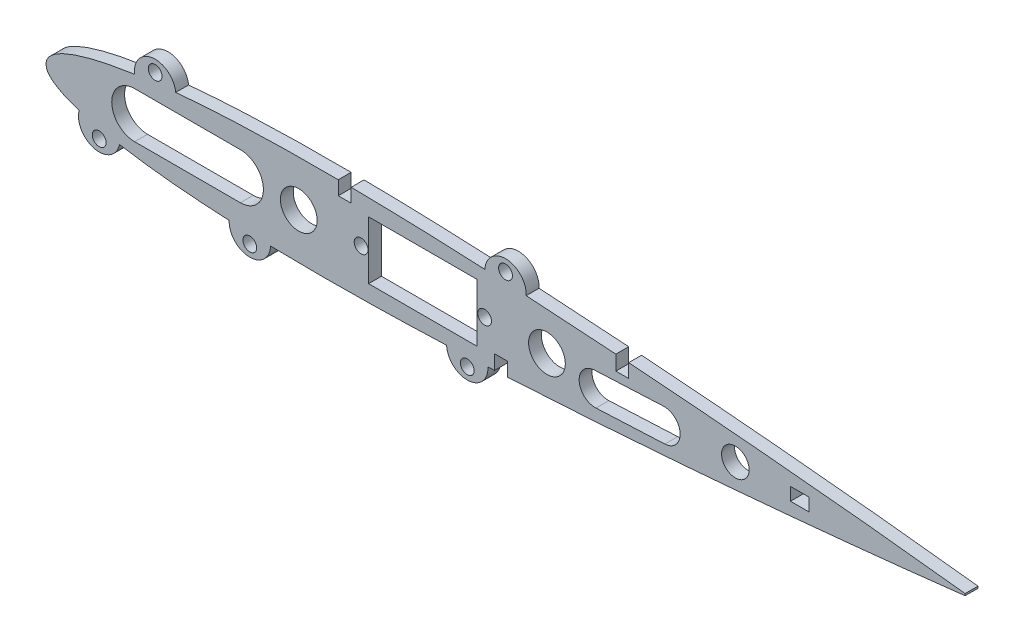
SolidWorks part; units mm, degrees
material "Фанера"
ref_plane "Спереди" through (0, 0, 0) normal (0, 0, 1) x (1, 0, 0)
ref_plane "Сверху" through (0, 0, 0) normal (0, 1, 0) x (1, 0, 0)
ref_plane "Справа" through (0, 0, 0) normal (1, 0, 0) x (0, 0, -1)
curve "Кривая1"
  spline degree 3 poles (200, 0.21, 0) (199.5201, 0.266, 0) (198.1795, 0.4223, 0) (195.7476, 0.7017, 0) (192.5308, 1.0651, 0) (188.7716, 1.4807, 0) (184.587, 1.9325, 0) (180.0562, 2.4092, 0) (175.2384, 2.9026, 0) (170.1814, 3.4057, 0) (164.925, 3.9132, 0) (159.5032, 4.4204, 0) (153.9461, 4.9234, 0) (148.2803, 5.4186, 0) (142.5299, 5.9028, 0) (136.7168, 6.3729, 0) (130.8615, 6.8262, 0) (124.9826, 7.2598, 0) (119.0976, 7.6711, 0) (113.2231, 8.0575, 0) (107.3746, 8.4163, 0) (101.5666, 8.7448, 0) (95.8133, 9.0407, 0) (90.1279, 9.3014, 0) (84.5231, 9.5247, 0) (79.0111, 9.7082, 0) (73.6037, 9.85, 0) (68.3121, 9.9482, 0) (63.1472, 10.0012, 0) (58.1196, 10.0077, 0) (53.2393, 9.9665, 0) (48.5164, 9.8771, 0) (43.9603, 9.7388, 0) (39.5803, 9.5517, 0) (35.3856, 9.3161, 0) (31.3849, 9.0325, 0) (27.5868, 8.7017, 0) (23.9997, 8.3252, 0) (20.6317, 7.9043, 0) (17.4909, 7.4408, 0) (14.5849, 6.9366, 0) (11.9213, 6.3939, 0) (9.5074, 5.8148, 0) (7.3502, 5.2016, 0) (5.4564, 4.5565, 0) (3.8315, 3.8815, 0) (2.4822, 3.178, 0) (1.4075, 2.4454, 0) (0.6238, 1.6789, 0) (0.1006, 0.8638, 0) (0.0324, 0.2785, 0) (0, 0, 0) knots 0 0 0 0 0.007145 0.019956 0.036196 0.055011 0.075879 0.098429 0.122376 0.147488 0.173572 0.20046 0.228005 0.256076 0.284555 0.313333 0.34231 0.371393 0.400496 0.429538 0.458442 0.487136 0.515552 0.543624 0.57129 0.598491 0.62517 0.651272 0.676746 0.701542 0.725611 0.748908 0.771388 0.793008 0.813728 0.833508 0.85231 0.870097 0.886836 0.902493 0.917037 0.930441 0.94268 0.953734 0.96359 0.972247 0.979722 0.986065 0.991385 0.995901 1 1 1 1
curve "Кривая2"
  spline degree 3 poles (0, 0, 0) (0.0324, -0.2785, 0) (0.1006, -0.8638, 0) (0.6238, -1.6789, 0) (1.4075, -2.4454, 0) (2.4822, -3.178, 0) (3.8315, -3.8815, 0) (5.4564, -4.5565, 0) (7.3502, -5.2016, 0) (9.5074, -5.8148, 0) (11.9213, -6.3939, 0) (14.5849, -6.9366, 0) (17.4909, -7.4408, 0) (20.6317, -7.9043, 0) (23.9997, -8.3252, 0) (27.5868, -8.7017, 0) (31.3849, -9.0325, 0) (35.3856, -9.3161, 0) (39.5803, -9.5517, 0) (43.9603, -9.7388, 0) (48.5164, -9.8771, 0) (53.2393, -9.9665, 0) (58.1196, -10.0077, 0) (63.1472, -10.0012, 0) (68.3121, -9.9482, 0) (73.6037, -9.85, 0) (79.0111, -9.7082, 0) (84.5231, -9.5247, 0) (90.1279, -9.3014, 0) (95.8133, -9.0407, 0) (101.5666, -8.7448, 0) (107.3746, -8.4163, 0) (113.2231, -8.0575, 0) (119.0976, -7.6711, 0) (124.9826, -7.2598, 0) (130.8615, -6.8262, 0) (136.7168, -6.3729, 0) (142.5299, -5.9028, 0) (148.2803, -5.4186, 0) (153.9461, -4.9234, 0) (159.5032, -4.4204, 0) (164.925, -3.9132, 0) (170.1814, -3.4057, 0) (175.2384, -2.9026, 0) (180.0562, -2.4092, 0) (184.587, -1.9325, 0) (188.7716, -1.4807, 0) (192.5308, -1.0651, 0) (195.7476, -0.7017, 0) (198.1795, -0.4223, 0) (199.5201, -0.266, 0) (200, -0.21, 0) knots 0 0 0 0 0.004099 0.008615 0.013935 0.020278 0.027753 0.03641 0.046266 0.05732 0.069559 0.082963 0.097507 0.113164 0.129903 0.14769 0.166492 0.186272 0.206992 0.228612 0.251092 0.274389 0.298458 0.323254 0.348728 0.37483 0.401509 0.42871 0.456376 0.484448 0.512864 0.541558 0.570462 0.599504 0.628607 0.65769 0.686667 0.715445 0.743924 0.771995 0.79954 0.826428 0.852512 0.877624 0.901571 0.924121 0.944989 0.963804 0.980044 0.992855 1 1 1 1
sketch "Эскиз3" plane through (0, 0, 0) normal (0, 0, 1) x (1, 0, 0)
  line L0 (200, 0.21) -> (200, -0.21)
  line L1 (63.6, 9.9908) -> (63.6, 6.9656)
  line L2 (63.6, 6.9656) -> (66.4, 6.9656)
  line L3 (66.4, 6.9656) -> (66.4, 9.9656)
  line L4 (97.6, -8.9469) -> (97.6, -5.8023)
  line L5 (97.6, -5.8023) -> (100.4, -5.8023)
  line L6 (100.4, -5.8023) -> (100.4, -8.8023)
  line L7 (124, 7.3263) -> (124, 4.1244)
  line L8 (124, 4.1244) -> (126.8, 4.1244)
  line L9 (126.8, 4.1244) -> (126.8, 7.1244)
  line L10 (19.3, 0) -> (42.3, 0) construction
  line L11 (19.3, 5) -> (42.3, 5)
  line L12 (19.3, -5) -> (42.3, -5)
  line L13 (93.8, 6.3) -> (97.07, 6.3) construction
  line L16 (119.5083, -1.5033) -> (134.4917, -0.7967) construction
  line L17 (119.3435, 1.9928) -> (134.3268, 2.6994)
  line L18 (119.6732, -4.9994) -> (134.6565, -4.2928)
  line L19 (70.2, 6.3) -> (93.8, 6.3)
  line L20 (70.2, 6.3) -> (70.2, -6.3)
  line L21 (70.2, -6.3) -> (93.8, -6.3)
  line L22 (93.8, 6.3) -> (93.8, -6.3)
  line L23 (97.07, 6.3) -> (97.07, -6.3) construction
  line L24 (97.07, -6.3) -> (93.8, -6.3) construction
  line L25 (70.2, 6.3) -> (66.93, 6.3) construction
  line L26 (66.93, 6.3) -> (66.93, -6.3) construction
  line L27 (66.93, -6.3) -> (70.2, -6.3) construction
  line L28 (70.2, 6.3) -> (93.8, -6.3) construction
  line L29 (93.8, 6.3) -> (70.2, -6.3) construction
  line L31 (162, 1.4) -> (166, 1.4)
  line L32 (162, 1.4) -> (162, -1.4)
  line L33 (162, -1.4) -> (166, -1.4)
  line L34 (166, 1.4) -> (166, -1.4)
  line L35 (162, 1.4) -> (166, -1.4) construction
  line L36 (162, -1.4) -> (166, 1.4) construction
  line L38 (168, 8.0416) -> (168, -5.3) construction
  line L39 (162.1702, -4.1702) -> (173.8395, -3.0408)
  line L40 (168, -10) -> (168, -13.6699) construction
  circle A0 centre (109, 0) radius 4
  circle A1 centre (55, 0) radius 4
  arc A2 (150, 5.2672) -> (150, -5.2672) centre (150, 0) ccw
  arc A3 (142.8327, 5.8745) -> (142.8327, -5.8745) centre (150, 0) ccw
  circle A4 centre (150, 0) radius 3
  arc A5 (19.3, 5) -> (19.3, -5) centre (19.3, 0) ccw
  arc A6 (42.3, -5) -> (42.3, 5) centre (42.3, 0) ccw
  arc A9 (119.3435, 1.9928) -> (119.6732, -4.9994) centre (119.5083, -1.5033) ccw
  arc A10 (134.6565, -4.2928) -> (134.3268, 2.6994) centre (134.4917, -0.7967) ccw
  circle A11 centre (68.565, 0) radius 1.5
  circle A12 centre (95.435, 0) radius 1.5
  arc A15 (39.8557, -9.5556) -> (48.8498, -9.8763) centre (44.3518, -9.7437) ccw
  arc A16 (7.2221, -5.1424) -> (15.9845, -7.176) centre (11.5706, -6.3) ccw
  arc A17 (104.4862, 8.5785) -> (95.4986, 9.0507) centre (99.9924, 8.8146) ccw
  arc A18 (87.1718, -9.4177) -> (96.1629, -9.0183) centre (91.6679, -9.2285) ccw
  arc A19 (28.2226, 8.7508) -> (19.2847, 7.7022) centre (23.7469, 8.2844) ccw
  circle A20 centre (23.7469, 10.2844) radius 1.5
  circle A21 centre (11.5706, -8.3) radius 1.5
  circle A22 centre (44.3518, -11.7437) radius 1.5
  circle A23 centre (91.6679, -11.2285) radius 1.5
  circle A24 centre (99.9924, 10.8146) radius 1.5
  spline S0 degree 3 poles (-2866.8305, -882.3911) (75.6044, 45.0391) (-5.5517, 7.9427) (0.6238, -1.6789) (1.4075, -2.4454) (2.4822, -3.178) (3.8315, -3.8815) (5.4564, -4.5565) (7.3502, -5.2016) (9.5074, -5.8148) (11.9213, -6.3939) (14.5849, -6.9366) (17.4909, -7.4408) (20.6317, -7.9043) (23.9997, -8.3252) (27.5868, -8.7017) (31.3849, -9.0325) (35.3856, -9.3161) (39.5803, -9.5517) (43.9603, -9.7388) (48.5164, -9.8771) (53.2393, -9.9665) (58.1196, -10.0077) (63.1472, -10.0012) (68.3121, -9.9482) (73.6037, -9.85) (79.0111, -9.7082) (84.5231, -9.5247) (90.1279, -9.3014) (95.8133, -9.0407) (101.5666, -8.7448) (107.3746, -8.4163) (113.2231, -8.0575) (119.0976, -7.6711) (124.9826, -7.2598) (130.8615, -6.8262) (136.7168, -6.3729) (142.5299, -5.9028) (148.2803, -5.4186) (153.9461, -4.9234) (161.2601, -4.2614) (168.3719, -3.5857) (175.2384, -2.9026) (180.0562, -2.4092) (184.587, -1.9325) (188.7716, -1.4807) (192.5308, -1.0651) (195.7476, -0.7017) (301.6592, 11.4655) (404.8468, 37.5696) (853.4293, -2918.2523) knots -0.150554 -0.150554 -0.150554 -0.150554 0.004099 0.008615 0.013935 0.020278 0.027753 0.03641 0.046266 0.05732 0.069559 0.082963 0.097507 0.113164 0.129903 0.14769 0.166492 0.186272 0.206992 0.228612 0.251092 0.274389 0.298458 0.323254 0.348728 0.37483 0.401509 0.42871 0.456376 0.484448 0.512864 0.541558 0.570462 0.599504 0.628607 0.65769 0.686667 0.715445 0.743924 0.771995 0.79954 0.852512 0.877624 0.901571 0.924121 0.944989 0.963804 0.980044 0.992855 2.540137 2.540137 2.540137 2.540137 only from (0, 0) to (200, -0.21) construction
  spline S1 degree 3 poles (698.5809, 1930.3494) (378.8303, -31.2176) (288.4583, -9.949) (195.7476, 0.7017) (192.5308, 1.0651) (188.7716, 1.4807) (184.587, 1.9325) (180.0562, 2.4092) (175.2384, 2.9026) (168.3719, 3.5857) (161.2601, 4.2614) (153.9461, 4.9234) (148.2803, 5.4186) (142.5299, 5.9028) (136.7168, 6.3729) (130.8615, 6.8262) (124.9826, 7.2598) (119.0976, 7.6711) (113.2231, 8.0575) (107.3746, 8.4163) (101.5666, 8.7448) (95.8133, 9.0407) (90.1279, 9.3014) (84.5231, 9.5247) (79.0111, 9.7082) (73.6037, 9.85) (68.3121, 9.9482) (63.1472, 10.0012) (58.1196, 10.0077) (53.2393, 9.9665) (48.5164, 9.8771) (43.9603, 9.7388) (39.5803, 9.5517) (35.3856, 9.3161) (31.3849, 9.0325) (27.5868, 8.7017) (23.9997, 8.3252) (20.6317, 7.9043) (17.4909, 7.4408) (14.5849, 6.9366) (11.9213, 6.3939) (9.5074, 5.8148) (7.3502, 5.2016) (5.4564, 4.5565) (3.8315, 3.8815) (2.4822, 3.178) (1.4075, 2.4454) (0.6238, 1.6789) (-4.8382, -6.8312) (57.468, -36.5773) (-1913.2646, 582.3208) knots -1.343661 -1.343661 -1.343661 -1.343661 0.007145 0.019956 0.036196 0.055011 0.075879 0.098429 0.122376 0.147488 0.20046 0.228005 0.256076 0.284555 0.313333 0.34231 0.371393 0.400496 0.429538 0.458442 0.487136 0.515552 0.543624 0.57129 0.598491 0.62517 0.651272 0.676746 0.701542 0.725611 0.748908 0.771388 0.793008 0.813728 0.833508 0.85231 0.870097 0.886836 0.902493 0.917037 0.930441 0.94268 0.953734 0.96359 0.972247 0.979722 0.986065 0.991385 0.995901 1.131551 1.131551 1.131551 1.131551 only from (200, 0.21) to (0, 0) construction
  spline S2 degree 3 poles (0, 0) (0.0324, -0.2785) (0.1006, -0.8638) (0.6238, -1.6789) (1.4075, -2.4454) (2.4822, -3.178) (3.8315, -3.8815) (5.4382, -4.549) (6.605, -4.9478) (7.2221, -5.1424) knots 0 0 0 0 0.004099 0.008615 0.013935 0.020278 0.027753 0.03641 0.045976 0.045976 0.045976 0.045976
  spline S3 degree 3 poles (200, 0.21) (199.5201, 0.266) (198.1795, 0.4223) (195.7476, 0.7017) (192.5308, 1.0651) (188.7716, 1.4807) (184.587, 1.9325) (180.0562, 2.4092) (175.2384, 2.9026) (168.3719, 3.5857) (161.2601, 4.2614) (153.9461, 4.9234) (148.2803, 5.4186) (142.5299, 5.9028) (136.7168, 6.3729) (131.4667, 6.7793) (128.1563, 7.0254) (126.8, 7.1244) knots 0 0 0 0 0.007145 0.019956 0.036196 0.055011 0.075879 0.098429 0.122376 0.147488 0.20046 0.228005 0.256076 0.284555 0.313333 0.34231 0.362417 0.362417 0.362417 0.362417
  spline S4 degree 3 poles (63.6, 9.9908) (63.4338, 9.9918) (61.5906, 10.0032) (58.1196, 10.0077) (53.2393, 9.9665) (48.5164, 9.8771) (43.9603, 9.7388) (39.5803, 9.5517) (35.3856, 9.3161) (31.6197, 9.0491) (29.2544, 8.8466) (28.2226, 8.7508) knots 0.674288 0.674288 0.674288 0.674288 0.676746 0.701542 0.725611 0.748908 0.771388 0.793008 0.813728 0.833508 0.848829 0.848829 0.848829 0.848829
  spline S5 degree 3 poles (100.4, -8.8023) (100.7825, -8.782) (103.1029, -8.6579) (107.3746, -8.4163) (113.2231, -8.0575) (119.0976, -7.6711) (124.9826, -7.2598) (130.8615, -6.8262) (136.7168, -6.3729) (142.5299, -5.9028) (148.2803, -5.4186) (153.9461, -4.9234) (158.5667, -4.5052) (161.296, -4.252) (162.1702, -4.1702) knots 0.5072 0.5072 0.5072 0.5072 0.512864 0.541558 0.570462 0.599504 0.628607 0.65769 0.686667 0.715445 0.743924 0.771995 0.79954 0.812524 0.812524 0.812524 0.812524
  spline S6 degree 3 poles (124, 7.3263) (122.3646, 7.4427) (118.7696, 7.6927) (113.2231, 8.0575) (108.3537, 8.3562) (105.4442, 8.5243) (104.4862, 8.5785) knots 0.376253 0.376253 0.376253 0.376253 0.400496 0.429538 0.458442 0.47263 0.47263 0.47263 0.47263
  spline S7 degree 3 poles (173.8395, -3.0408) (175.9433, -2.8302) (179.564, -2.461) (184.587, -1.9325) (188.7716, -1.4807) (192.5308, -1.0651) (195.7476, -0.7017) (198.1795, -0.4223) (199.5201, -0.266) (200, -0.21) knots 0.870307 0.870307 0.870307 0.870307 0.901571 0.924121 0.944989 0.963804 0.980044 0.992855 1 1 1 1
  spline S8 degree 3 poles (19.2847, 7.7022) (18.662, 7.6113) (17.0675, 7.3673) (14.5849, 6.9366) (11.9213, 6.3939) (9.5074, 5.8148) (7.3502, 5.2016) (5.4564, 4.5565) (3.8315, 3.8815) (2.4822, 3.178) (1.4075, 2.4454) (0.6238, 1.6789) (0.1006, 0.8638) (0.0324, 0.2785) (0, 0) knots 0.893188 0.893188 0.893188 0.893188 0.902493 0.917037 0.930441 0.94268 0.953734 0.96359 0.972247 0.979722 0.986065 0.991385 0.995901 1 1 1 1
  spline S9 degree 3 poles (15.9845, -7.176) (16.462, -7.2592) (17.9845, -7.5136) (20.6317, -7.9043) (23.9997, -8.3252) (27.5868, -8.7017) (31.3849, -9.0325) (35.3856, -9.3161) (38.2323, -9.476) (39.7438, -9.5502) (39.8557, -9.5556) knots 0.090341 0.090341 0.090341 0.090341 0.097507 0.113164 0.129903 0.14769 0.166492 0.186272 0.206992 0.208649 0.208649 0.208649 0.208649
  spline S10 degree 3 poles (48.8498, -9.8763) (50.2955, -9.9107) (53.3689, -9.9676) (58.1196, -10.0077) (63.1472, -10.0012) (68.3121, -9.9482) (73.6037, -9.85) (79.0111, -9.7082) (83.5467, -9.5572) (86.2784, -9.4531) (87.1718, -9.4177) knots 0.253007 0.253007 0.253007 0.253007 0.274389 0.298458 0.323254 0.348728 0.37483 0.401509 0.42871 0.441931 0.441931 0.441931 0.441931
  spline S11 degree 3 poles (96.1629, -9.0183) (96.642, -8.9949) (97.121, -8.9711) (97.6, -8.9469) knots 0.486289 0.486289 0.486289 0.486289 0.493381 0.493381 0.493381 0.493381
  spline S12 degree 3 poles (95.4986, 9.0507) (93.6994, 9.1376) (90.0308, 9.3053) (84.5231, 9.5247) (79.0111, 9.7082) (73.6037, 9.85) (69.4115, 9.9278) (67.0232, 9.9585) (66.4, 9.9656) knots 0.516989 0.516989 0.516989 0.516989 0.543624 0.57129 0.598491 0.62517 0.651272 0.660487 0.660487 0.660487 0.660487
  point P17 (65, 6.9656)
  point P20 (99, -5.8023)
  point P30 (30.8, 0)
  point P42 (127, -1.15)
  point P50 (82, 0)
  point P55 (68.565, 6.3)
  point P56 (95.435, 6.3)
  point P57 (164, 0)
  dimension "D1" = 8
  dimension "D2" = 8
  dimension "D16" = 5.2672
  dimension "D17" = 9.2672
  dimension "D18" = 6
  dimension "D32" = 3
  dimension "D33" = 3
  dimension "D37" = 3
  dimension "D3" = 109
  dimension "D4" = 55
  dimension "D5" = 2.8
  dimension "D6" = 2.8
  dimension "D7" = 2.8
  dimension "D8" = 10
  dimension "D9" = 10
  dimension "D10" = 15
  dimension "D11" = 3
  dimension "D12" = 3
  dimension "D13" = 3
  dimension "D14" = 150
  dimension "D15" = 10.5344
  dimension "D21" = 23
  dimension "D22" = 10
  dimension "D23" = 19.3
  dimension "D27" = 18
  dimension "D28" = 7
  dimension "D29" = 2.7
  dimension "D26" = 15
  dimension "D30" = 1.15
  dimension "D19" = 12.6
  dimension "D20" = 23.6
  dimension "D24" = 3.27
  dimension "D25" = 3.27
  dimension "D31" = 27
  dimension "D34" = 2.8
  dimension "D35" = 4
  dimension "D36" = 14
  dimension "D39" = 18
  dimension "D40" = 10
  dimension "D38" = 2
  dimension "D41" = 2
  dimension "D42" = 2
  dimension "D43" = 2
  dimension "D44" = 2
extrude "Бобышка-Вытянуть3" add sketch "Эскиз3" along normal blind 2.8
equation "\"D16@Эскиз3\"=\"D15@Эскиз3\"/2"
equation "\"D17@Эскиз3\"=\"D16@Эскиз3\"+4"
